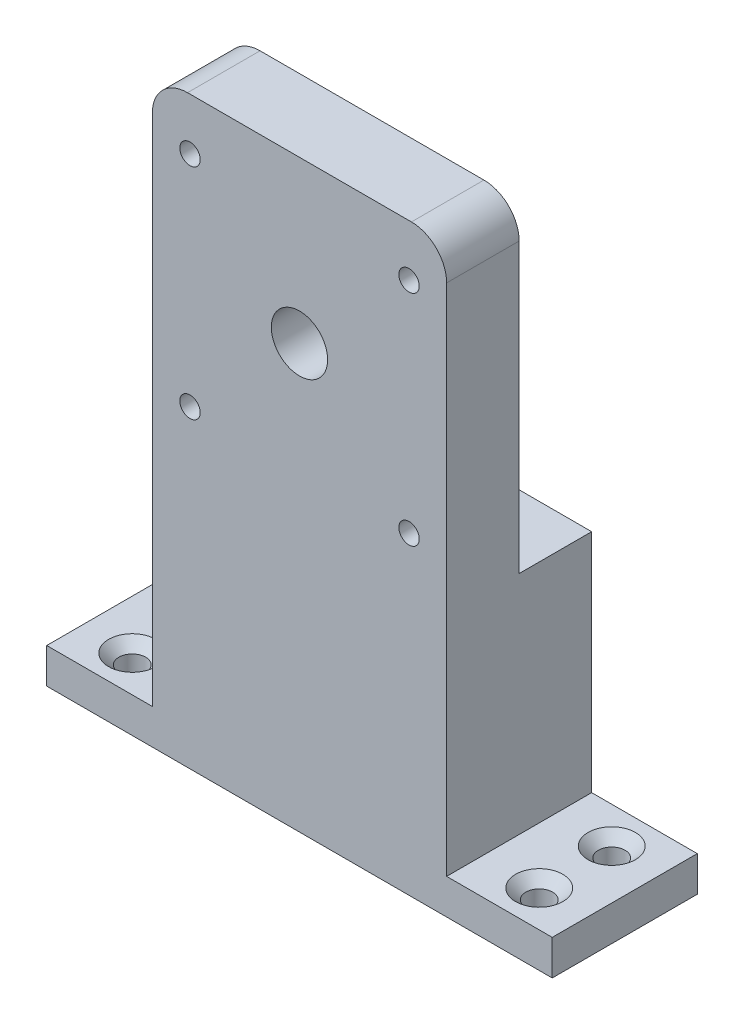
SolidWorks part; units mm, degrees
ref_plane "Ön Düzlem" through (0, 0, 0) normal (0, 0, 1) x (1, 0, 0)
ref_plane "Üst Düzlem" through (0, 0, 0) normal (0, 1, 0) x (1, 0, 0)
ref_plane "Sağ Düzlem" through (0, 0, 0) normal (1, 0, 0) x (0, 0, -1)
sketch "Çizim1" plane through (0, 0, 0) normal (0, 0, 1) x (1, 0, 0)
  line L0 (-35.9, 0) -> (35.9, 0)
  line L7 (20.9, 5) -> (20.9, 78)
  line L8 (-20.9, 5) -> (-20.9, 78)
  line L11 (-15.9, 83) -> (15.9, 83)
  line L12 (35.9, 0) -> (35.9, 5)
  line L13 (35.9, 5) -> (20.9, 5)
  line L15 (-35.9, 0) -> (-35.9, 5)
  line L16 (-35.9, 5) -> (-20.9, 5)
  circle A0 centre (0, 60.1) radius 4
  circle A1 centre (-15.55, 75.65) radius 1.45
  circle A2 centre (15.56, 75.65) radius 1.45
  circle A3 centre (15.56, 44.54) radius 1.45
  circle A4 centre (-15.55, 44.54) radius 1.45
  arc A5 (-20.9, 78) -> (-15.9, 83) centre (-15.9, 78) cw
  arc A6 (20.9, 78) -> (15.9, 83) centre (15.9, 78) ccw
  dimension "D1" = 5
  dimension "D2" = 5
extrude "Yükseklik-Ekstrüzyon1" add sketch "Çizim1" along normal blind 10.3
sketch "Çizim2" plane through (0, 5, 0) normal (0, 1, 0) x (1, 0, 0)
  line L0 (35.9, -5.15) -> (28.9, -5.15) construction
  line L1 (35.9, -10.3) -> (35.9, 0) construction
  line L2 (-35.9, -5.15) -> (-28.9, -5.15) construction
  line L3 (-35.9, -10.3) -> (-35.9, 0) construction
  circle A0 centre (28.9, -5.15) radius 1.9
  circle A1 centre (-28.9, -5.15) radius 1.9
extrude "Kes-Ekstrüzyon1" cut sketch "Çizim2" against normal blind 10.3
hole_wizard "M3 Altıgen Alyan Havşa Başlı Kör Vida İçin Havşa1" positions "3B Çizim1" profile "Çizim3" countersink size "M3" standard "ISO" end condition through all
sketch3d "3B Çizim1"
  line L0 (-28.9, 0, 5.15) -> (-28.9, 5, 5.15) construction
  line L1 (28.9, 0, 5.15) -> (28.9, 5, 5.15) construction
  point P0 (-28.9, 5, 5.15)
  point P4 (28.9, 5, 5.15)
sketch "Çizim3" plane through (-28.9, 5, 5.15) normal (1, 0, 0) x (0, 0, 1)
  line L0 (0, 0) -> (0, 5)
  line L1 (0, 5) -> (1.8, 5)
  line L2 (1.8, 5) -> (1.8, 1.56)
  line L3 (1.8, 1.56) -> (3.36, 0)
  line L5 (3.36, 0) -> (0, 0)
  line L6 (-1.8, 1.56) -> (-3.36, 0) construction
  line L11 (0, -6.35) -> (0, 107.95) construction
  dimension "Thru Hole Dia." = 3.6
  dimension "Thru Hole Depth" = 5
  dimension "Near C'Sink Dia." = 6.72
  dimension "Near C'Sink Angle" = 90
sketch "Çizim4" plane through (0, 0, 0) normal (0, 0, -1) x (-1, 0, 0)
  circle A0 centre (0, 60.1) radius 11
extrude "Kes-Ekstrüzyon2" cut sketch "Çizim4" against normal blind 2
sketch "Çizim5" plane through (0, 0, 0) normal (0, 0, -1) x (-1, 0, 0)
  line L0 (-20.9, 37.1) -> (20.9, 37.1)
  line L1 (0, 39.2) -> (0, 81) construction
  line L2 (20.9, 37.1) -> (20.9, 5)
  line L3 (20.9, 60.1) -> (-20.9, 60.1) construction
  line L4 (20.9, 78) -> (20.9, 5) construction
  line L5 (20.9, 37.1) -> (-20.9, 37.1) construction
  line L6 (-20.9, 5) -> (-20.9, 78) construction
  line L7 (20.9, 5) -> (35.9, 5)
  line L8 (35.9, 5) -> (35.9, 0)
  line L9 (35.9, 0) -> (-35.9, 0)
  line L10 (-35.9, 0) -> (-35.9, 5)
  line L11 (-35.9, 5) -> (-20.9, 5)
  line L12 (-20.9, 5) -> (-20.9, 37.1)
extrude "Yükseklik-Ekstrüzyon2" add sketch "Çizim5" along normal blind 10.3
sketch "Çizim6" plane through (0, 5, 0) normal (0, 1, 0) x (1, 0, 0)
  circle A1 centre (28.9, 5.15) radius 1.9
  circle A2 centre (-28.9, 5.15) radius 1.9
extrude "Kes-Ekstrüzyon3" cut sketch "Çizim6" against normal blind 10.3
hole_wizard "M3 Altıgen Alyan Havşa Başlı Kör Vida İçin Havşa3" positions "3B Çizim3" profile "Çizim8" countersink size "M3" standard "ISO" end condition through all
sketch3d "3B Çizim3"
  line L0 (-28.9, 0, -5.15) -> (-28.9, 5, -5.15) construction
  line L1 (28.9, 0, -5.15) -> (28.9, 5, -5.15) construction
  point P0 (-28.9, 5, -5.15)
  point P4 (28.9, 5, -5.15)
sketch "Çizim8" plane through (-28.9, 5, -5.15) normal (1, 0, 0) x (0, 0, 1)
  line L0 (0, 0) -> (0, 5)
  line L1 (0, 5) -> (1.8, 5)
  line L2 (1.8, 5) -> (1.8, 1.56)
  line L3 (1.8, 1.56) -> (3.36, 0)
  line L5 (3.36, 0) -> (0, 0)
  line L6 (-1.8, 1.56) -> (-3.36, 0) construction
  line L11 (0, -6.35) -> (0, 107.95) construction
  dimension "Thru Hole Dia." = 3.6
  dimension "Thru Hole Depth" = 5
  dimension "Near C'Sink Dia." = 6.72
  dimension "Near C'Sink Angle" = 90
